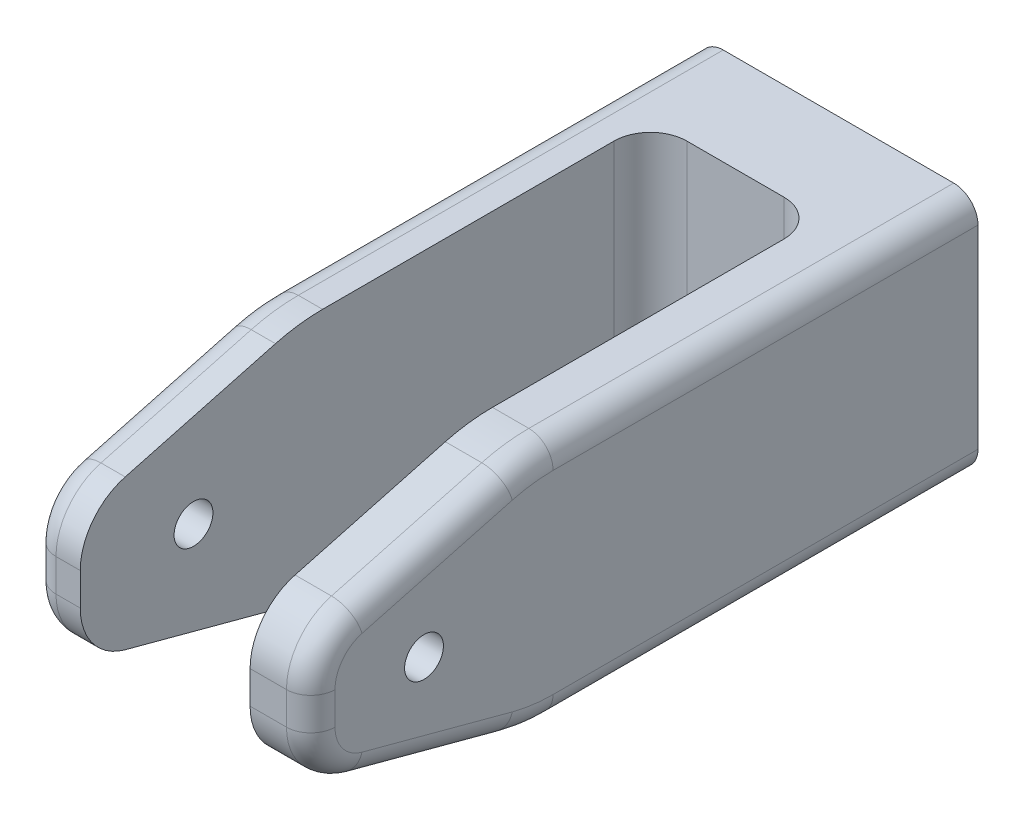
SolidWorks part; units mm, degrees
ref_plane "Front Plane" through (0, 0, 0) normal (0, 0, 1) x (1, 0, 0)
ref_plane "Top Plane" through (0, 0, 0) normal (0, 1, 0) x (1, 0, 0)
ref_plane "Right Plane" through (0, 0, 0) normal (1, 0, 0) x (0, 0, -1)
ref_plane "Plane1" through (-1089.9507, 0, 0) normal (-1, 0, 0) x (0, 0, 1)
sketch "Sketch1" plane through (-1089.9507, 0, 0) normal (-1, 0, 0) x (0, 0, 1)
  line L0 (82.0041, 86.4772) -> (82.0041, 83.7966)
  line L1 (27.0041, 95.1369) -> (64.0041, 95.1369)
  line L2 (27.0041, 95.1369) -> (27.0041, 75.1369)
  line L3 (27.0041, 75.1369) -> (64.0041, 75.1369)
  line L7 (27.0041, 85.1369) -> (72.6679, 85.1369) construction
  line L8 (64.0041, 75.1369) -> (78.2982, 78.967)
  line L9 (64.0041, 95.1369) -> (78.2982, 91.3068)
  circle A2 centre (72.6679, 85.1369) radius 1.6
  arc A3 (78.2982, 78.967) -> (82.0041, 83.7966) centre (77.0041, 83.7966) ccw
  arc A4 (78.2982, 91.3068) -> (82.0041, 86.4772) centre (77.0041, 86.4772) cw
  point P6 (83.0041, 89.6867)
  point P8 (83.0041, 78.7225)
  dimension "D5" = 165
  dimension "D6" = 165
  dimension "D8" = 5
  dimension "D1" = 55
  dimension "D2" = 10
  dimension "D3" = 18
  dimension "D4" = 18
  dimension "D7" = 10
extrude "Boss-Extrude1" add sketch "Sketch1" along normal mid plane 5
sketch "Sketch2" plane through (-1106.4507, 0, 0) normal (-1, 0, 0) x (0, 0, 1)
  line L6 (27.0041, 95.1369) -> (27.0041, 75.1369)
  line L7 (27.0041, 75.1369) -> (64.0041, 75.1369)
  line L8 (64.0041, 75.1369) -> (78.2982, 78.967)
  line L9 (82.0041, 83.7966) -> (82.0041, 86.4772)
  line L10 (78.2982, 91.3068) -> (64.0041, 95.1369)
  line L11 (64.0041, 95.1369) -> (27.0041, 95.1369)
  line L12 (27.0041, 95.1369) -> (27.0041, 75.1369)
  line L13 (27.0041, 75.1369) -> (64.0041, 75.1369)
  line L14 (64.0041, 75.1369) -> (78.2982, 78.967)
  line L16 (78.2982, 91.3068) -> (64.0041, 95.1369)
  line L17 (64.0041, 95.1369) -> (27.0041, 95.1369)
  line L18 (82.0041, 83.7966) -> (82.0041, 86.4772)
  circle A0 centre (72.6679, 85.1369) radius 1.6 construction
  circle A1 centre (72.6679, 85.1369) radius 1.6
  arc A6 (78.2982, 78.967) -> (82.0041, 83.7966) centre (77.0041, 83.7966) ccw
  arc A7 (78.2982, 78.967) -> (82.0041, 83.7966) centre (77.0041, 83.7966) ccw
  arc A8 (82.0041, 86.4772) -> (78.2982, 91.3068) centre (77.0041, 86.4772) ccw
  arc A9 (82.0041, 86.4772) -> (78.2982, 91.3068) centre (77.0041, 86.4772) ccw
  dimension "D1" = 0
extrude "Boss-Extrude2" add sketch "Sketch2" along normal blind 4 separate body
sketch "Sketch3" plane through (0, 0, 27.0041) normal (0, 0, -1) x (-1, 0, 0)
  line L1 (1087.4507, 95.1369) -> (1110.4507, 95.1369)
  line L2 (1087.4507, 95.1369) -> (1087.4507, 75.1369)
  line L3 (1087.4507, 75.1369) -> (1110.4507, 75.1369)
  line L4 (1110.4507, 95.1369) -> (1110.4507, 75.1369)
extrude "Boss-Extrude3" add sketch "Sketch3" against normal blind 8
fillet "Fillet1" radius 3 2 edges at (-1106.4507, 85.1369, 35.0041) (-1092.4507, 85.1369, 35.0041)
fillet "Fillet2" radius 15 4 edges at (-1108.4507, 95.1369, 64.0041) (-1089.9507, 95.1369, 64.0041) (-1108.4507, 75.1369, 64.0041) (-1089.9507, 75.1369, 64.0041)
fillet "Fillet3" radius 2 18 edges at (-1110.4507, 95.1369, 44.5167) (-1110.4507, 95.0086, 63.9872) (-1110.4507, 92.9663, 72.1049) (-1110.4507, 77.3075, 72.1049) (-1110.4507, 75.2652, 63.9872) (-1087.4507, 95.1369, 44.5167) (-1087.4507, 95.0086, 63.9872) (-1087.4507, 92.9663, 72.1049) (-1087.4507, 77.3075, 72.1049) (-1087.4507, 75.2652, 63.9872) (-1110.4507, 75.1369, 44.5167) (-1087.4507, 75.1369, 44.5167) (-1110.4507, 89.521, 80.9708) (-1110.4507, 85.1369, 82.0041) (-1110.4507, 80.7528, 80.9708) (-1087.4507, 89.521, 80.9708) (-1087.4507, 85.1369, 82.0041) (-1087.4507, 80.7528, 80.9708)
